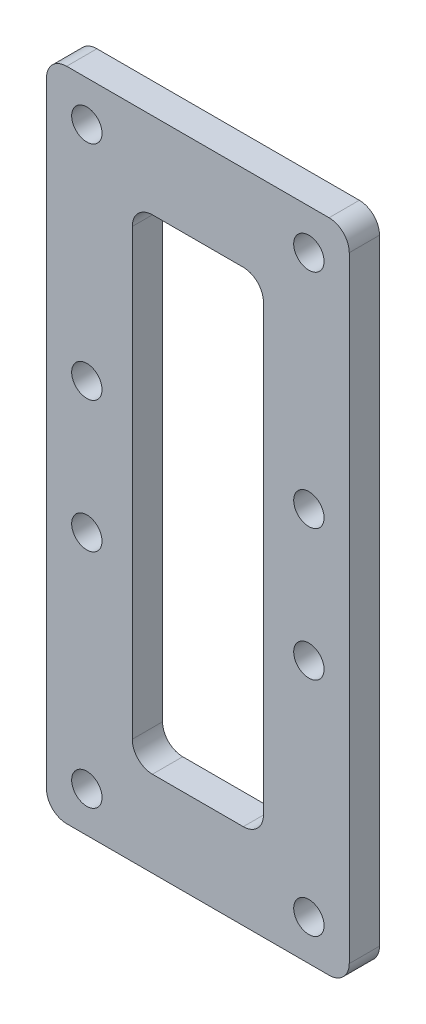
SolidWorks part; units mm, degrees
material "Thornel Mat VMA"
ref_plane "前视基准面" through (0, 0, 0) normal (0, 0, 1) x (1, 0, 0)
ref_plane "上视基准面" through (0, 0, 0) normal (0, 1, 0) x (1, 0, 0)
ref_plane "右视基准面" through (0, 0, 0) normal (1, 0, 0) x (0, 0, -1)
sketch "草图1" plane through (0, 0, 0) normal (0, 0, 1) x (1, 0, 0)
  line L1 (-15, -32.5) -> (15, -32.5)
  line L2 (-15, -32.5) -> (-15, 32.5)
  line L3 (-15, 32.5) -> (15, 32.5)
  line L4 (15, -32.5) -> (15, 32.5)
  line L5 (0, 32.5) -> (0, -32.5) construction
  line L6 (-15, 0) -> (15, 0) construction
  point P0 (0, 0)
  dimension "D1" = 65
  dimension "D2" = 30
extrude "凸台-拉伸1" add sketch "草图1" along normal blind 3
sketch "草图2" plane through (0, 0, 3) normal (0, 0, 1) x (1, 0, 0)
  line L0 (0, 0) -> (0, 32.5) construction
  line L1 (15, 32.5) -> (-15, 32.5) construction
  line L2 (15, -32.5) -> (15, 32.5) construction
  line L3 (-11, 6.5) -> (11, 6.5) construction
  line L4 (-11, 6.5) -> (-11, 28.5) construction
  line L5 (-11, 28.5) -> (11, 28.5) construction
  line L6 (11, 6.5) -> (11, 28.5) construction
  line L7 (0, 28.5) -> (0, 6.5) construction
  line L8 (-11, 17.5) -> (11, 17.5) construction
  circle A0 centre (-11, 28.5) radius 1.505
  circle A1 centre (11, 28.5) radius 1.505
  circle A2 centre (-11, 6.5) radius 1.505
  circle A3 centre (11, 6.5) radius 1.505
  point P5 (0, 17.5)
  dimension "D3" = 3.01
  dimension "D1" = 4
  dimension "D2" = 4
  dimension "D4" = 22
extrude "切除-拉伸1" cut sketch "草图2" against normal blind 3
mirror "镜向1" about plane through (0, 0, 0) normal (0, 1, 0) of "切除-拉伸1"
fillet "圆角1" radius 2 4 edges at (15, -32.5, 1.5) (-15, -32.5, 1.5) (-15, 32.5, 1.5) (15, 32.5, 1.5)
sketch "草图3" plane through (0, 0, 3) normal (0, 0, 1) x (1, 0, 0)
  line L1 (-6.5, -24) -> (6.5, -24)
  line L2 (-6.5, -24) -> (-6.5, 24)
  line L3 (-6.5, 24) -> (6.5, 24)
  line L4 (6.5, -24) -> (6.5, 24)
  line L5 (0, 24) -> (0, -24) construction
  line L6 (-6.5, 0) -> (6.5, 0) construction
  circle A0 centre (11, 6.5) radius 1.505 construction
  circle A1 centre (11, 28.5) radius 1.505 construction
  point P0 (0, 0)
  dimension "D1" = 4.5
  dimension "D2" = 4.5
extrude "切除-拉伸2" cut sketch "草图3" against normal blind 10
fillet "圆角2" radius 2 4 edges at (-6.5, 24, 1.5) (6.5, 24, 1.5) (-6.5, -24, 1.5) (6.5, -24, 1.5)
